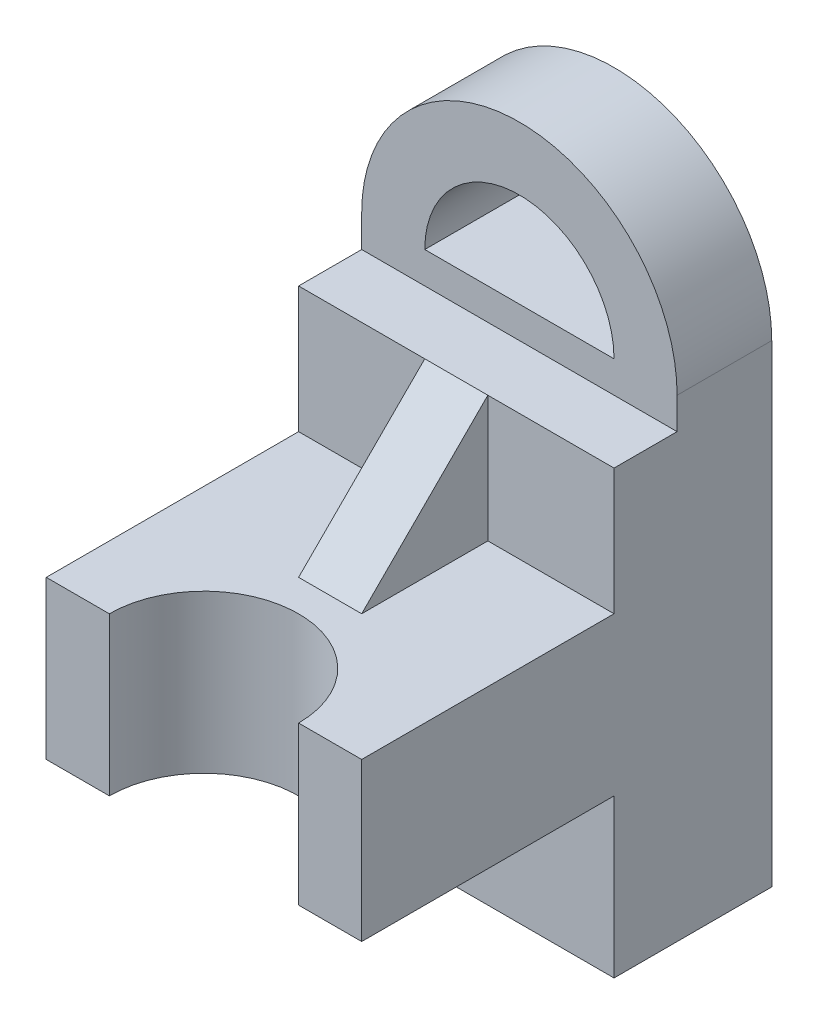
SolidWorks part; units mm, degrees
ref_plane "Front Plane" through (0, 0, 0) normal (0, 0, 1) x (1, 0, 0)
ref_plane "Top Plane" through (0, 0, 0) normal (0, 1, 0) x (1, 0, 0)
ref_plane "Right Plane" through (0, 0, 0) normal (1, 0, 0) x (0, 0, -1)
sketch "Sketch2" plane through (0, 0, 0) normal (0, 0, 1) x (1, 0, 0)
  line L1 (-80.7878, 0) -> (104.5254, 0) construction
  line L8 (-25, 37.5) -> (-25, -37.5)
  line L9 (-25, -37.5) -> (25, -37.5)
  line L10 (25, 37.5) -> (25, -37.5)
  line L11 (-25, 37.5) -> (25, -37.5) construction
  line L12 (-25, -37.5) -> (25, 37.5) construction
  line L13 (0, 67.7404) -> (0, -83.4614) construction
  arc A1 (25, 37.5) -> (-25, 37.5) centre (0, 37.5) ccw
  point P5 (0, 0)
  point P6 (0, 0)
extrude "Boss-Extrude2" add sketch "Sketch2" along normal blind 15
sketch "Sketch4" plane through (0, 0, 15) normal (0, 0, 1) x (1, 0, 0)
  line L0 (0, 65.2952) -> (0, -45.5167) construction
  line L1 (-36.8406, 0) -> (37.4208, 0) construction
  line L2 (0, 62.5) -> (0, 37.5)
  line L3 (-15, 37.5) -> (15, 37.5)
  arc A0 (25, 37.5) -> (-25, 37.5) centre (0, 37.5) ccw construction
  arc A1 (15, 37.5) -> (-15, 37.5) centre (0, 37.5) ccw
extrude "Cut-Extrude2" cut sketch "Sketch4" against normal blind 15 contours A1 L3
sketch "Sketch5" plane through (0, 0, 15) normal (0, 0, 1) x (1, 0, 0)
  line L0 (0, 66.6006) -> (0, -40.2952) construction
  line L1 (-39.7415, 0) -> (39.4514, 0) construction
  line L2 (25, -37.5) -> (25, 37.5) construction
  line L3 (-25, -37.5) -> (25, -37.5)
  line L4 (-25, -37.5) -> (-25, 32.5)
  line L5 (-25, 32.5) -> (25, 32.5)
  line L6 (25, -37.5) -> (25, 32.5)
extrude "Boss-Extrude3" add sketch "Sketch5" along normal blind 10 contours L4 L3 L6 L5
sketch "Sketch6" plane through (-25, 0, 0) normal (-1, 0, 0) x (0, 0, 1)
  line L3 (25, -37.5) -> (25, 32.5) construction
  line L4 (25, -12.5) -> (65, -12.5)
  line L5 (25, -12.5) -> (25, 12.5)
  line L6 (25, 12.5) -> (65, 12.5)
  line L7 (65, -12.5) -> (65, 12.5)
extrude "Boss-Extrude4" add sketch "Sketch6" against normal blind 50
sketch "Sketch10" plane through (0, 0, 0) normal (1, 0, 0) x (0, 0, -1)
  line L0 (-25, 32.5) -> (-45, 12.5)
  line L1 (-65, 12.5) -> (-25, 12.5) construction
rib "Rib1" sketch "Sketch10" sketch "Sketch10" thickness 10 extrusion direction parallel to sketch draft on no parameters "D1"=10
sketch "Sketch11" plane through (0, 12.5, 0) normal (0, 1, 0) x (1, 0, 0)
  line L0 (25, -65) -> (-25, -65) construction
  circle A0 centre (0, -65) radius 15
extrude "Cut-Extrude3" cut sketch "Sketch11" against normal blind 25
